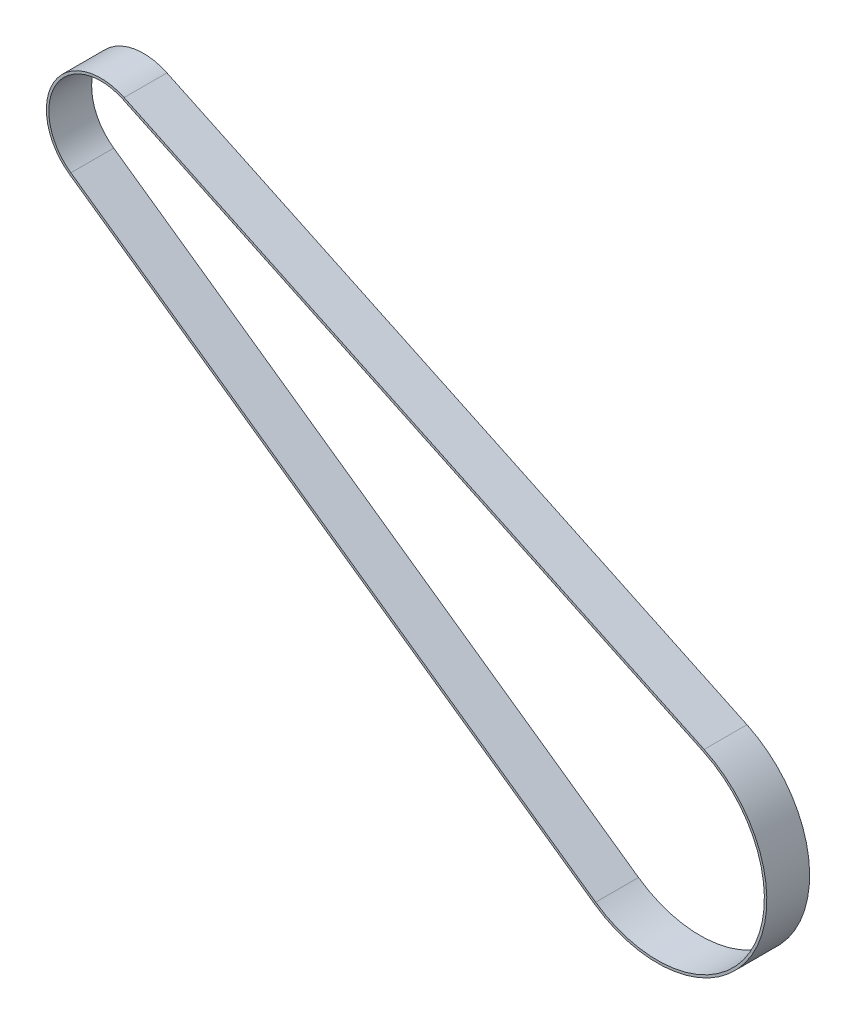
SolidWorks part; units mm, degrees
ref_plane "Front Plane" through (0, 0, 0) normal (0, 0, 1) x (1, 0, 0)
ref_plane "Top Plane" through (0, 0, 0) normal (0, 1, 0) x (1, 0, 0)
ref_plane "Right Plane" through (0, 0, 0) normal (1, 0, 0) x (0, 0, -1)
sketch "Sketch1" plane through (0, 0, 0) normal (0, 0, 1) x (1, 0, 0)
  line L0 (0, 0) -> (0, 336.55) construction
  line L1 (0, 0) -> (577.57, 0) construction
  line L2 (0, 336.55) -> (577.57, 0) construction
  line L3 (625.1039, 100.4455) -> (23.0879, 385.3378)
  line L4 (513.619, -90.8792) -> (-31.0619, 292.4087)
  line L5 (626.1904, 102.7414) -> (24.1744, 387.6337)
  line L6 (512.1572, -92.9565) -> (-32.5237, 290.3314)
  arc A0 (513.619, -90.8792) -> (625.1039, 100.4455) centre (577.57, 0) ccw
  arc A1 (23.0879, 385.3378) -> (-31.0619, 292.4087) centre (0, 336.55) ccw
  arc A2 (24.1744, 387.6337) -> (-32.5237, 290.3314) centre (0, 336.55) ccw
  arc A3 (512.1572, -92.9565) -> (626.1904, 102.7414) centre (577.57, 0) ccw
  dimension "D1" = 222.25
  dimension "D2" = 107.95
  dimension "D3" = 336.55
  dimension "D4" = 577.57
  dimension "D5" = 2.54
extrude "Boss-Extrude1" add sketch "Sketch1" along normal blind 44.45
